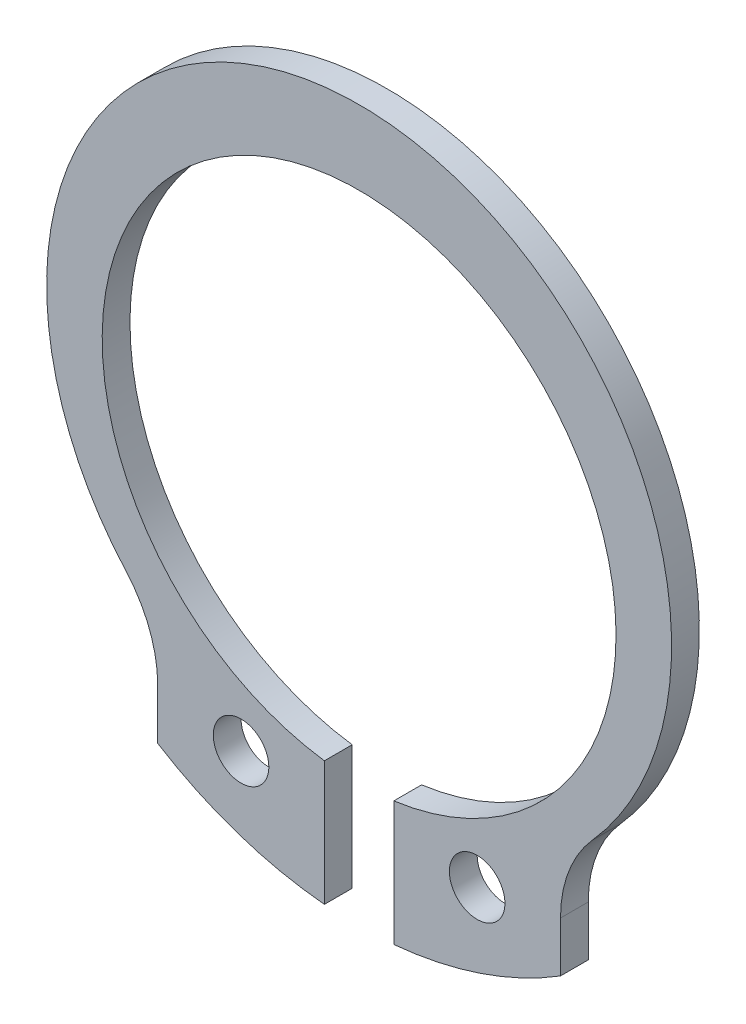
SolidWorks part; units mm, degrees
ref_plane "Front" through (0, 0, 0) normal (0, 0, 1) x (1, 0, 0)
ref_plane "Top" through (0, 0, 0) normal (0, 1, 0) x (1, 0, 0)
ref_plane "Right" through (0, 0, 0) normal (1, 0, 0) x (0, 0, -1)
sketch "Sketch1" plane through (0, 0, 0) normal (0, 0, 1) x (1, 0, 0)
  line L0 (0, 4.2365) -> (0, -4.2365) construction
  line L1 (-1.25, -14.3129) -> (-1.25, -9.8352)
  line L2 (1.25, -14.3129) -> (1.25, -9.8352)
  line L3 (-4.25, -3.2292) -> (-4.25, -11.0323) construction
  line L4 (-7.25, -8.6023) -> (-7.25, -12.2944)
  line L5 (7.25, -8.6023) -> (7.25, -12.2944)
  line L6 (4.25, -3.2292) -> (4.25, -11.0323) construction
  line L7 (11.2, -0.67) -> (-11.2, -0.67) construction
  line L8 (0, -0.67) -> (-1.8514, -14.2443) construction
  arc A0 (1.25, -9.8352) -> (-1.25, -9.8352) centre (0, -0.67) ccw
  arc A1 (7.25, -8.6023) -> (-7.25, -8.6023) centre (0, 0) ccw
  arc A2 (-11.2, -0.67) -> (11.2, -0.67) centre (0, -0.67) ccw construction
  circle A3 centre (-4.25, -11.0323) radius 1
  arc A4 (-7.25, -12.2944) -> (-1.25, -14.3129) centre (0, -0.67) ccw
  circle A5 centre (4.25, -11.0323) radius 1
  arc A6 (7.25, -12.2944) -> (1.25, -14.3129) centre (0, -0.67) cw
  dimension "d0" = 18.5
  dimension "D" = 22.5
  dimension "d1" = 2
  dimension "R1" = 11.2
  dimension "B1" = 2.5
  dimension "c" = 0.67
  dimension "L" = 14.5
  dimension "B2" = 8.5
  dimension "a" = 4.45
extrude "Body" add sketch "Sketch1" against normal blind 1
fillet "Fillet1" radius 4.5 2 edges at (-7.25, -8.6023, -0.5) (7.25, -8.6023, -0.5)
